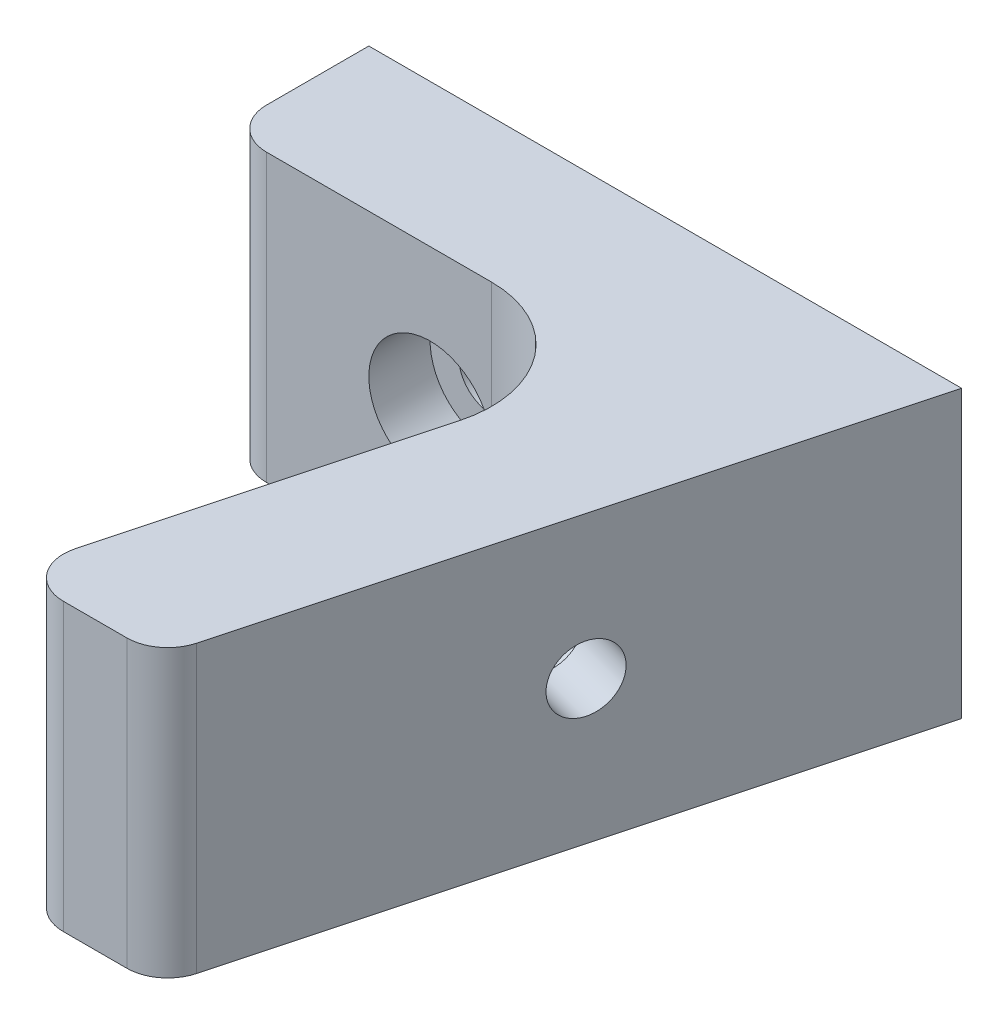
SolidWorks part; units mm, degrees
material "ABS"
ref_plane "Front" through (0, 0, 0) normal (0, 0, 1) x (1, 0, 0)
ref_plane "Top" through (0, 0, 0) normal (0, 1, 0) x (1, 0, 0)
ref_plane "Right" through (0, 0, 0) normal (1, 0, 0) x (0, 0, -1)
sketch "Esquisse1" plane through (0, 0, 0) normal (0, 1, 0) x (1, 0, 0)
  line L0 (-10, 0) -> (-10, -7)
  line L1 (-10, 0) -> (19, 0)
  line L3 (3.4466, -31) -> (10.6936, -31)
  line L4 (19, 0) -> (10.6936, -31)
  line L5 (-10, -7) -> (3, -7)
  line L6 (8.0974, -13.6431) -> (3.4466, -31)
  arc A0 (3, -7) -> (8.0974, -13.6431) centre (3, -12.2772) cw
  dimension "D5" = 3
  dimension "D1" = 10
  dimension "D2" = 19
  dimension "D3" = 75
  dimension "D4" = 31
  dimension "D6" = 7
  dimension "D7" = 7
extrude "Boss.-Extru.1" add sketch "Esquisse1" along normal mid plane 14
hole_wizard "Chambrage pour vis à tête cylindrique à 6 pans creux (ou vis CHC) M31" positions "Esquisse3" profile "Esquisse4" counterbore size "M3" standard "Ansi Metric" end condition through all
sketch "Esquisse3" plane through (0, 0, 7) normal (0, 0, 1) x (1, 0, 0)
  point P0 (0, 0)
sketch "Esquisse4" plane through (0, 0, 7) normal (1, 0, 0) x (0, -1, 0)
  line L0 (0, 0) -> (0, 7)
  line L1 (0, 7) -> (1.6, 7)
  line L3 (1.6, 7) -> (1.6, 3)
  line L4 (1.6, 3) -> (3, 3)
  line L5 (3, 3) -> (3, 0)
  line L7 (3, 0) -> (0, 0)
  line L11 (0, -6.35) -> (0, 107.95) construction
  dimension "Diamètre du perçage jusqu'au prochain" = 3.2
  dimension "Profondeur du perçage jusqu'au prochain" = 7
  dimension "Diamètre du chambrage" = 6
  dimension "Profondeur du chambrage" = 3
fillet "Congé1" radius 2 3 edges at (10.6936, 0, 31) (-10, 0, 7) (3.4466, 0, 31)
sketch "Esquisse5" plane through (17.7272, 0, 4.75) normal (0.9659, 0, 0.2588) x (0.2588, 0, -0.9659)
  line L0 (4.9176, 7) -> (4.9176, -7) construction
  circle A0 centre (-10.0824, 0) radius 1.6
  dimension "D1" = 3.2
  dimension "D2" = 15
extrude "Enlèv. mat.-Extru.1" cut sketch "Esquisse5" against normal blind 10
sketch "Esquisse6" plane through (17.7272, 0, 4.75) normal (0.9659, 0, 0.2588) x (0.2588, 0, -0.9659)
  line L1 (-7.3324, 1.5877) -> (-10.0824, 3.1754)
  line L2 (-10.0824, 3.1754) -> (-12.8324, 1.5877)
  line L3 (-12.8324, 1.5877) -> (-12.8324, -1.5877)
  line L4 (-12.8324, -1.5877) -> (-10.0824, -3.1754)
  line L5 (-10.0824, -3.1754) -> (-7.3324, -1.5877)
  line L6 (-7.3324, -1.5877) -> (-7.3324, 1.5877)
  circle A0 centre (-10.0824, 0) radius 2.75 construction
  dimension "D1" = 5.5
extrude "Enlèv. mat.-Extru.2" cut sketch "Esquisse6" against normal blind 7 from offset 3
